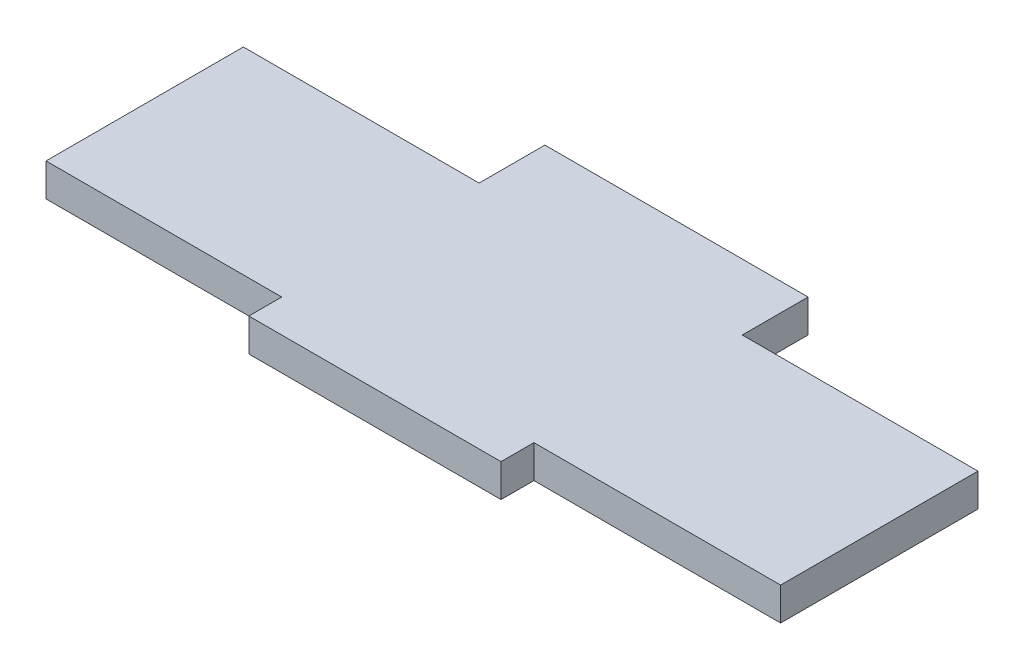
SolidWorks part; units mm, degrees
ref_plane "Front Plane" through (0, 0, 0) normal (0, 0, 1) x (1, 0, 0)
ref_plane "Top Plane" through (0, 0, 0) normal (0, 1, 0) x (1, 0, 0)
ref_plane "Right Plane" through (0, 0, 0) normal (1, 0, 0) x (0, 0, -1)
sketch "Sketch1" plane through (0, 0, 0) normal (0, 1, 0) x (1, 0, 0)
  line L1 (-66.9945, 18) -> (0, 18)
  line L2 (-66.9945, 18) -> (-66.9945, 0)
  line L3 (-66.9945, 0) -> (0, 0)
  line L4 (0, 18) -> (0, 0)
  line L5 (-45.4972, 18) -> (-21.4972, 18)
  line L6 (-45.4972, 18) -> (-45.4972, 24)
  line L7 (-45.4972, 24) -> (-21.4972, 24)
  line L8 (-21.4972, 18) -> (-21.4972, 24)
  line L9 (-45.4972, 0) -> (-21.4972, 0)
  line L10 (-45.4972, 0) -> (-45.4972, -3)
  line L11 (-45.4972, -3) -> (-21.4972, -3)
  line L12 (-21.4972, 0) -> (-21.4972, -3)
  line L13 (-21.4972, 0) -> (-22.4972, 0)
  line L14 (-21.4972, 0) -> (-21.4972, -3)
  line L15 (-21.4972, -3) -> (-22.4972, -3)
  line L16 (-22.4972, 0) -> (-22.4972, -3)
  point P13 (-33.4972, -3)
  point P14 (-33.4972, 0)
  dimension "D1" = 18
  dimension "D2" = 66.9945
  dimension "D3" = 24
  dimension "D4" = 3
  dimension "D5" = 6
  dimension "D6" = 1
extrude "Boss-Extrude1" add sketch "Sketch1" along normal blind 3 contours L12 L3 L10 L11 | L4 L1 L2 L3 | L1 L8 L7 L6
equation "\"D2@Sketch1\"=\"x\""
equation "\"x\"= 67 / ( cos ( \"angle\" ) ) - \"thick\" * cos ( 90 - \"angle\" )"
equation "\"angle\"= 5"
equation "\"thick\"=3"
equation "\"D1@Boss-Extrude1\"=\"thick\""
